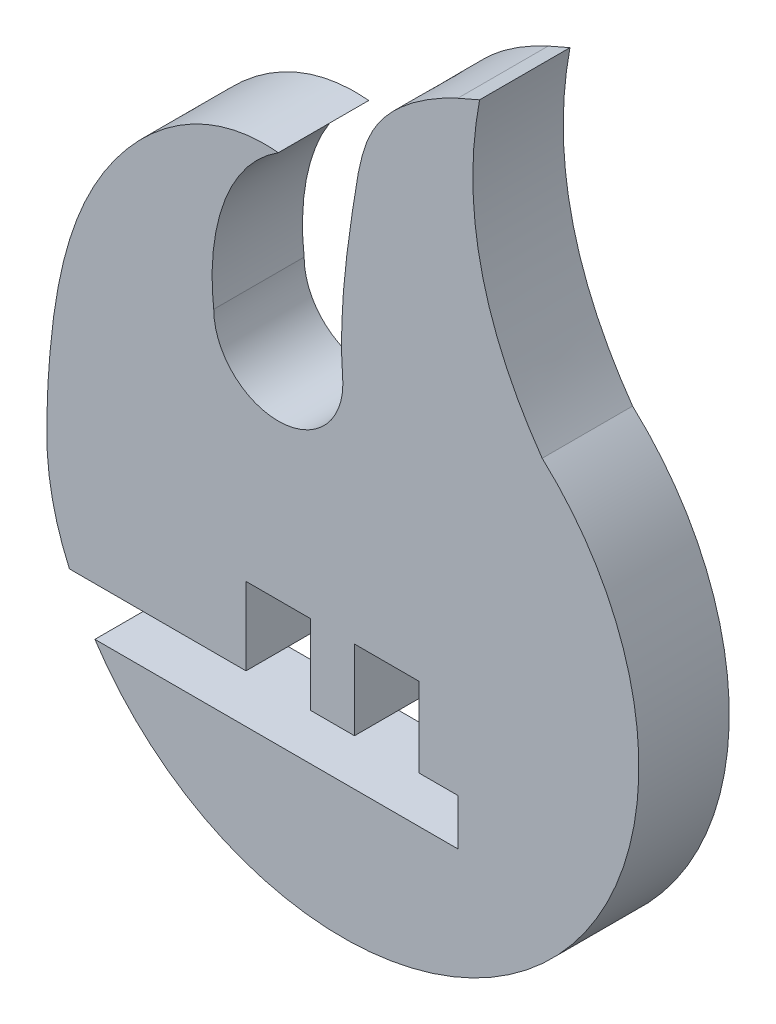
SolidWorks part; units mm, degrees
ref_plane "Front Plane" through (0, 0, 0) normal (0, 0, 1) x (1, 0, 0)
ref_plane "Top Plane" through (0, 0, 0) normal (0, 1, 0) x (1, 0, 0)
ref_plane "Right Plane" through (0, 0, 0) normal (1, 0, 0) x (0, 0, -1)
sketch "Sketch1" plane through (0, 0, 0) normal (0, 0, 1) x (1, 0, 0)
  line L6 (0, 0) -> (0, 0.6153)
  line L7 (0, 0.6153) -> (-0.5, 0.6153)
  line L8 (-0.5, 0.6153) -> (-0.5, 0.0153)
  line L9 (-0.5, 0.0153) -> (-1.8674, 0.0153)
  line L10 (0, 0) -> (0.34, 0)
  line L11 (0.34, 0) -> (0.34, 0.6153)
  line L12 (0.34, 0.6153) -> (0.84, 0.6153)
  line L13 (0.84, 0.6153) -> (0.84, 0)
  line L14 (0.84, 0) -> (1.14, 0)
  line L15 (-0.25, 0.6153) -> (-0.25, 1.8153) construction
  line L16 (-0.25, 0.6153) -> (-0.25, 3.6153) construction
  line L17 (1.14, 0) -> (1.14, -0.3584)
  line L18 (1.14, -0.3584) -> (-1.6704, -0.3584)
  line L19 (-2.76, -0.1784) -> (-1.16, -0.1784) construction
  arc A0 (-0.75, 2.3153) -> (0.25, 2.3153) centre (-0.25, 2.3153) ccw
  arc A1 (-1.6704, -0.3584) -> (1.7936, 2.5875) centre (0.25, 0.893) ccw
  spline S0 degree 3 poles (-0.25, 3.6153) (-0.678, 3.3432) (-0.8075, 2.7882) (-0.75, 2.3153) knots 0 0 0 0 1 1 1 1
  spline S1 degree 3 poles (-2.0392, 0.7099) (-2.0471, 0.9256) (-2.0222, 1.6041) (-1.7894, 2.8648) (-0.8552, 3.6749) (-0.25, 3.6153) knots 0.156243 0.156243 0.156243 0.156243 0.300823 0.609121 1 1 1 1
  spline S2 degree 3 poles (0.25, 2.3153) (0.2155, 2.7569) (0.2949, 3.3429) (0.4424, 4.2585) (0.8789, 4.5551) (1.14, 4.6756) knots 0 0 0 0 0.483638 0.672292 1 1 1 1
  spline S4 degree 3 poles (-1.8674, 0.0153) (-1.9672, 0.2359) (-2.0244, 0.4674) (-2.0392, 0.71) knots 0 0 0 0 0.800781 0.800781 0.800781 0.800781
  spline S5 degree 2 poles (1.14, 4.6756) (1.2243, 4.7124) (1.3086, 4.7491) knots 0 0 0 0.865242 0.865242 0.865242
  spline S6 degree 2 poles (1.3086, 4.7491) (1.0892, 3.5852) (1.7936, 2.5875) knots 0 0 0 1 1 1
  point P1 (0, 0)
  dimension "D9" = 1
  dimension "D3" = 0.6
  dimension "D4" = 0.18
  dimension "D6" = 0.34
  dimension "D7" = 0.3
  dimension "D8" = 1.2
  dimension "D10" = 3
  dimension "D12" = 1.6
  dimension "D13" = 2.3
extrude "Boss-Extrude1" add sketch "Sketch1" along normal blind 0.7 contours S6 S5 S2 A0 S0 S1 S4 L9 L8 L7 L6 L10 L11 L12 L13 L14 L17 L18 A1
scale "Scale1" scale about centroid uniform scaling yes scale factor 3
